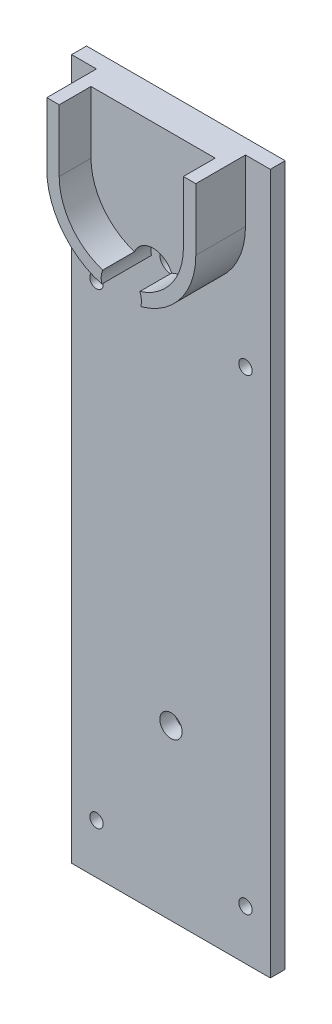
SolidWorks part; units mm, degrees
ref_plane "Piano frontale" through (0, 0, 0) normal (0, 0, 1) x (1, 0, 0)
ref_plane "Piano superiore" through (0, 0, 0) normal (0, 1, 0) x (1, 0, 0)
ref_plane "Piano destro" through (0, 0, 0) normal (1, 0, 0) x (0, 0, -1)
sketch "Schizzo1" plane through (0, 0, 0) normal (0, 0, 1) x (1, 0, 0)
  line L0 (-15.3297, 65.5) -> (15.3297, 65.5)
  line L1 (20, -70.5) -> (-20, -70.5)
  line L3 (20, 70.5) -> (-20, 70.5)
  line L5 (20, -13.4286) -> (-20, 13.4286) construction
  line L6 (20, 13.4286) -> (-20, -13.4286) construction
  line L8 (0, 65.5) -> (0, -2.5) construction
  line L9 (0, -2.5) -> (0, -70.5) construction
  line L10 (-20, 70.5) -> (20, 70.5)
  line L11 (-20, 70.5) -> (-20, -70.5)
  line L12 (-20, -70.5) -> (20, -70.5)
  line L13 (20, 70.5) -> (20, -70.5)
  line L14 (-20, 70.5) -> (20, -70.5) construction
  line L15 (-20, -70.5) -> (20, 70.5) construction
  arc A0 (15.3297, 65.5) -> (-15.3297, 65.5) centre (0, 44.5) ccw
  circle A1 centre (0, 44.5) radius 2.25
  circle A2 centre (0, -36.5) radius 2.25
  point P0 (0, 0)
  point P8 (0, 70.5)
  point P16 (0, 0)
  dimension "D3" = 52
  dimension "D5" = 4.5
  dimension "D1" = 141
  dimension "D4" = 5
  dimension "D6" = 40
extrude "Estrusione-Estrusione4" add sketch "Schizzo1" along normal blind 3 contours A0 L0 L10 L11 L1 L13 L3 A2 A1 | L0 A0
sketch "Schizzo2" plane through (0, 0, 3) normal (0, 0, 1) x (1, 0, 0)
  line L1 (20, 70.5) -> (-20, 70.5) construction
  line L3 (15, 58) -> (15, 70.5)
  line L4 (-12.5, 58) -> (-12.5, 70.5)
  line L5 (-15, 58) -> (-15, 70.5)
  line L6 (12.5, 58) -> (12.5, 70.5)
  line L7 (-12.5, 70.5) -> (-15, 70.5)
  line L8 (12.5, 70.5) -> (15, 70.5)
  arc A0 (-12.5, 58) -> (-3.7331, 46.0705) centre (0, 58) ccw
  arc A1 (-15, 58) -> (-3.9307, 43.5242) centre (0, 58) ccw
  arc A4 (3.9307, 43.5242) -> (15, 58) centre (0, 58) ccw
  arc A5 (3.7331, 46.0705) -> (12.5, 58) centre (0, 58) ccw
  arc A7 (-3.7331, 46.0705) -> (-3.9307, 43.5242) centre (0, 44.5) ccw
  arc A8 (3.9307, 43.5242) -> (3.7331, 46.0705) centre (0, 44.5) ccw
  point P7 (0, 70.5)
  dimension "D1" = 25
  dimension "D2" = 30
  dimension "D3" = 8.1
extrude "Estrusione-Estrusione5" add sketch "Schizzo2" along normal blind 10
sketch "Schizzo3" plane through (0, 0, 3) normal (0, 0, 1) x (1, 0, 0)
  line L0 (15, 58) -> (15, 70.5) construction
  line L1 (15, 70.5) -> (12.5, 70.5) construction
  line L2 (12.5, 70.5) -> (12.5, 58) construction
  line L3 (-12.5, 58) -> (-12.5, 70.5) construction
  line L4 (-12.5, 70.5) -> (-15, 70.5) construction
  line L5 (-15, 70.5) -> (-15, 58) construction
  line L6 (15, 58) -> (15, 70.5)
  line L7 (15, 70.5) -> (12.5, 70.5)
  line L8 (12.5, 70.5) -> (12.5, 58)
  line L9 (-12.5, 58) -> (-12.5, 70.5)
  line L10 (-12.5, 70.5) -> (-15, 70.5)
  line L11 (-15, 70.5) -> (-15, 58)
  line L12 (-12.5, 70.5) -> (12.5, 70.5)
  arc A0 (3.9307, 43.5242) -> (15, 58) centre (0, 58) ccw construction
  arc A1 (3.7331, 46.0705) -> (12.5, 58) centre (0, 58) ccw construction
  arc A2 (3.9307, 43.5242) -> (3.7331, 46.0705) centre (0, 44.5) ccw construction
  arc A3 (-15, 58) -> (-3.9307, 43.5242) centre (0, 58) ccw construction
  arc A4 (-3.7331, 46.0705) -> (-3.9307, 43.5242) centre (0, 44.5) ccw construction
  arc A5 (-12.5, 58) -> (-3.7331, 46.0705) centre (0, 58) ccw construction
  arc A6 (3.9307, 43.5242) -> (15, 58) centre (0, 58) ccw
  arc A7 (3.7331, 46.0705) -> (12.5, 58) centre (0, 58) ccw
  arc A8 (3.9307, 43.5242) -> (3.7331, 46.0705) centre (0, 44.5) ccw
  arc A9 (-15, 58) -> (-3.9307, 43.5242) centre (0, 58) ccw
  arc A10 (-3.7331, 46.0705) -> (-3.9307, 43.5242) centre (0, 44.5) ccw
  arc A11 (-12.5, 58) -> (-3.7331, 46.0705) centre (0, 58) ccw
  circle A12 centre (0, 44.5) radius 4.05
  arc M7 (3.7331, 46.0705) -> (12.5, 58) centre (0, 58) ccw
  line M8 (12.5, 58) -> (12.5, 70.5)
  line M9 (12.5, 70.5) -> (-12.5, 70.5)
  line M10 (-12.5, 70.5) -> (-12.5, 58)
  arc M11 (-12.5, 58) -> (-3.7331, 46.0705) centre (0, 58) ccw
extrude "Estrusione-Estrusione6" add sketch "Schizzo3" along normal blind 3.6 contours A12 M7 M8 M9 M10 M11
hole_wizard "Foro per Vite M2.5-1" positions "Schizzo3D1" profile "Schizzo4" hole size "M2.5" standard "ISO" end condition through all
sketch3d "Schizzo3D1"
  line L0 (0, -70.5, 3) -> (-10, -70.5, 3) construction
  line L1 (20, -70.5, 3) -> (-20, -70.5, 3) construction
  line L2 (-10, -70.5, 3) -> (-20, -70.5, 3) construction
  line L4 (-15, -70.5, 3) -> (-15, 43.5242, 3) construction
  line L5 (-15, 43.5242, 3) -> (-3.9307, 43.5242, 3) construction
  line L7 (-15, -70.5, 3) -> (-15, -60.5, 3) construction
  line L9 (-15, 43.5242, 3) -> (-15, 33.5242, 3) construction
  point P0 (-15, 33.5242, 3)
  point P17 (-15, -60.5, 3)
  point P27 (-15, -60.5, 3)
  point P29 (-15, -60.5, 3)
  point P32 (0, 0, 0)
  dimension "D1" = 10
  dimension "D2" = 10
  dimension "D3" = 10
sketch "Schizzo4" plane through (-15, 33.5242, 3) normal (1, 0, 0) x (0, -1, 0)
  line L0 (0, 0) -> (0, 3)
  line L1 (0, 3) -> (1.35, 3)
  line L2 (1.35, 3) -> (1.35, 0)
  line L5 (1.35, 0) -> (0, 0)
  line L11 (0, -6.35) -> (0, 107.95) construction
  dimension "Thru Hole Dia." = 2.7
  dimension "Thru Hole Depth" = 3
mirror "Specchia1" about plane through (0, 0, 0) normal (1, 0, 0) of "Foro per Vite M2.5-1"
